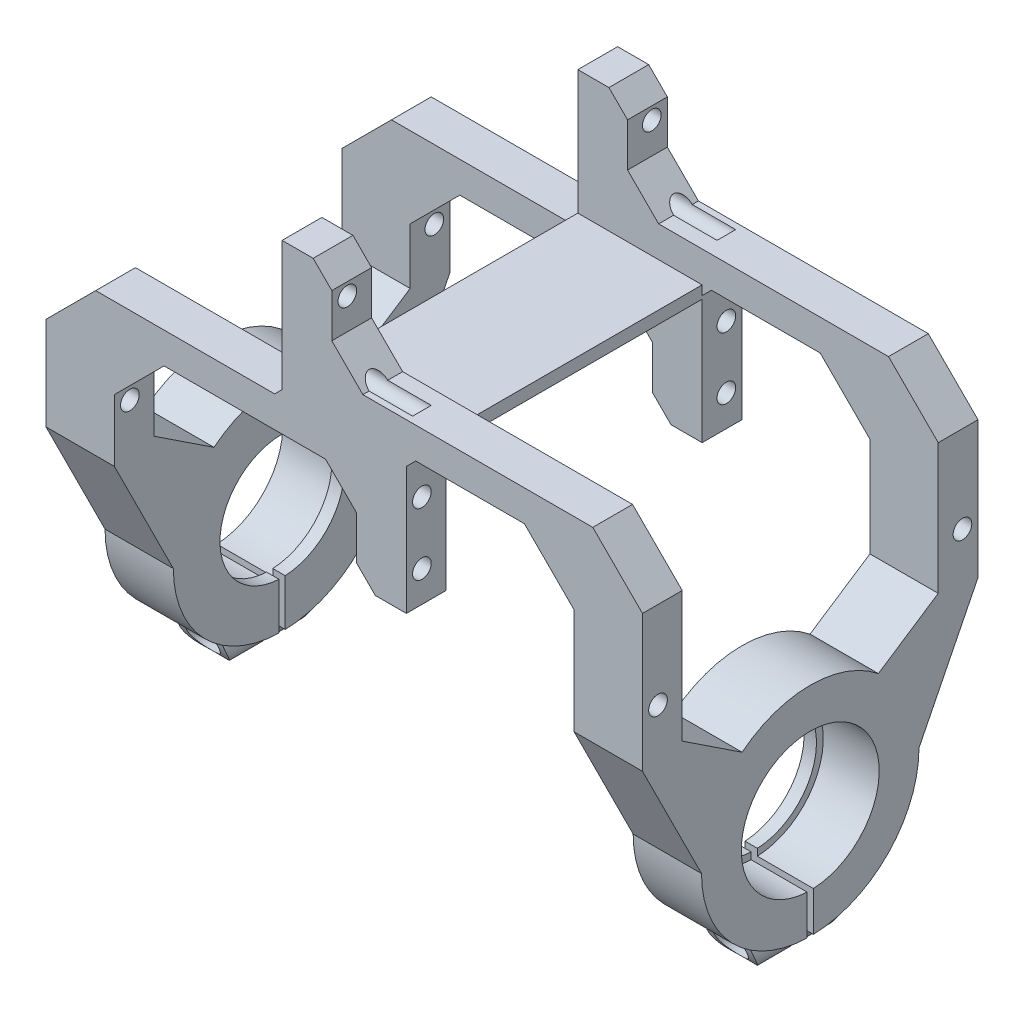
SolidWorks part; units mm, degrees
ref_plane "Front Plane" through (0, 0, 0) normal (0, 0, 1) x (1, 0, 0)
ref_plane "Top Plane" through (0, 0, 0) normal (0, 1, 0) x (1, 0, 0)
ref_plane "Right Plane" through (0, 0, 0) normal (1, 0, 0) x (0, 0, -1)
sketch "Sketch1" plane through (0, 0, 0) normal (0, 1, 0) x (1, 0, 0)
  line L1 (-10, -27) -> (10, -27)
  line L2 (-10, -27) -> (-10, 27)
  line L3 (-10, 27) -> (10, 27)
  line L4 (10, -27) -> (10, 27)
  line L5 (-10, -27) -> (10, 27) construction
  line L6 (-10, 27) -> (10, -27) construction
  point P0 (0, 0)
  dimension "D1" = 54
  dimension "D2" = 20
extrude "Boss-Extrude1" add sketch "Sketch1" along normal blind 2
sketch "Sketch2" plane through (0, 2, 0) normal (0, 1, 0) x (1, 0, 0)
  line L1 (-10, 27) -> (-2, 27)
  line L2 (-10, 27) -> (-10, 20.6)
  line L3 (-10, 20.6) -> (-2, 20.6)
  line L4 (-2, 27) -> (-2, 20.6)
  line L5 (-10, 27) -> (-2, 20.6) construction
  line L6 (-10, 20.6) -> (-2, 27) construction
  line L7 (-10, -27) -> (-2, -27)
  line L8 (-10, -27) -> (-10, -20.6)
  line L9 (-10, -20.6) -> (-2, -20.6)
  line L10 (-2, -27) -> (-2, -20.6)
  line L11 (-10, -27) -> (-2, -20.6) construction
  line L12 (-10, -20.6) -> (-2, -27) construction
  point P4 (-6, 23.8)
  point P10 (-6, -23.8)
  dimension "D1" = 6.4
  dimension "D2" = 8
  dimension "D3" = 8
  dimension "D4" = 6.4
extrude "Boss-Extrude2" add sketch "Sketch2" along normal blind 20
chamfer "Chamfer1" distance 5 angle 45 2 edges at (-2, 2, -23.8) (-2, 2, 23.8)
sketch "Sketch3" plane through (0, 0, 0) normal (0, -1, 0) x (1, 0, 0)
  line L1 (10, 27) -> (2, 27)
  line L2 (10, 27) -> (10, 20.6)
  line L3 (10, 20.6) -> (2, 20.6)
  line L4 (2, 27) -> (2, 20.6)
  line L5 (10, 27) -> (2, 20.6) construction
  line L6 (10, 20.6) -> (2, 27) construction
  line L7 (10, -27) -> (2, -27)
  line L8 (10, -27) -> (10, -20.6)
  line L9 (10, -20.6) -> (2, -20.6)
  line L10 (2, -27) -> (2, -20.6)
  line L11 (10, -27) -> (2, -20.6) construction
  line L12 (10, -20.6) -> (2, -27) construction
  point P4 (6, 23.8)
  point P10 (6, -23.8)
  dimension "D1" = 8
  dimension "D2" = 6.4
  dimension "D3" = 6.4
  dimension "D4" = 8
extrude "Boss-Extrude3" add sketch "Sketch3" along normal blind 20
chamfer "Chamfer2" distance 5 angle 45 2 edges at (2, 0, 23.8) (2, 0, -23.8)
chamfer "Chamfer3" distance 3 angle 45 4 edges at (2, -20, -23.8) (2, -20, 23.8) (-2, 22, -23.8) (-2, 22, 23.8)
sketch "Sketch5" plane through (0, 0, -27) normal (0, 0, -1) x (-1, 0, 0)
  line L0 (-10, 2) -> (-48, 2)
  line L1 (2, 7) -> (-48, 7)
  line L2 (-48, 7) -> (-48, 2)
  line L3 (2, 7) -> (-3, 2) construction
  line L4 (-10, 2) -> (-3, 2) construction
  line L5 (2, 7) -> (-3, 2)
  line L6 (-10, 2) -> (-3, 2)
  line L7 (0, 0) -> (0, 20) construction
  dimension "D1" = 48
  dimension "D2" = 20
extrude "Boss-Extrude4" add sketch "Sketch5" against normal up to surface (6.4 mm away) up to face at (-4.3333, 12.3333, -20.6)
sketch "Sketch7" plane through (0, 0, 27) normal (0, 0, 1) x (1, 0, 0)
  line L0 (3, 2) -> (-2, 7) construction
  line L1 (3, 2) -> (-2, 7)
  line L8 (-2, 7) -> (-2, 19)
  line L9 (-2, 19) -> (-5, 22)
  line L10 (-5, 22) -> (-10, 22)
  line L11 (-10, 22) -> (-10, 2)
  line L12 (-10, 2) -> (10, 2)
  line L13 (10, 2) -> (48, 2)
  line L14 (48, 2) -> (48, 7)
  line L15 (48, 7) -> (-2, 7)
  line L16 (-2, 7) -> (-2, 19)
  line L17 (-2, 19) -> (-5, 22)
  line L18 (-5, 22) -> (-10, 22)
  line L19 (-10, 22) -> (-10, 2)
  line L20 (-10, 2) -> (10, 2)
  line L21 (10, 2) -> (48, 2)
  line L22 (48, 2) -> (48, 7)
  line L23 (48, 7) -> (-2, 7)
  line M13 (10, 2) -> (3, 2)
  line M14 (3, 2) -> (-2, 7)
  dimension "D1" = 0
extrude "Boss-Extrude6" add sketch "Sketch7" against normal up to surface (6.4 mm away) contours L22 L23 L21 M14 M13 up to face at (-4.3333, 12.3333, 20.6)
chamfer "Chamfer4" distance 5 angle 45 2 edges at (-2, 7, -23.8) (-2, 7, 23.8)
chamfer "Chamfer5" distance 1.5 angle 45 2 edges at (10, 2, 23.8) (10, 2, -23.8)
sketch "Sketch6" plane through (48, 0, 0) normal (1, 0, 0) x (0, 0, -1)
  line L0 (27, 2) -> (27, -23)
  line L1 (27, -23) -> (17.5, -42)
  line L2 (20.6, 2) -> (20.6, -22)
  line L3 (20.6, 2) -> (27, 2) construction
  line L4 (20.6, 2) -> (27, 2)
  line L5 (20.6, -22) -> (10.9653, -28.3614)
  line L6 (0, 0) -> (0, 30) construction
  line L7 (-20.6, 0) -> (20.6, 0) construction
  line L8 (-20.6, -22) -> (-10.9653, -28.3614)
  line L9 (-20.6, 2) -> (-27, 2)
  line L10 (-20.6, 2) -> (-20.6, -22)
  line L11 (-27, -23) -> (-17.5, -42)
  line L12 (-27, 2) -> (-27, -23)
  arc A0 (10.9653, -28.3614) -> (-10.9653, -28.3614) centre (0, -42) ccw
  circle A1 centre (0, -42) radius 11.1
  arc A2 (-17.5, -42) -> (17.5, -42) centre (0, -42) ccw
  dimension "D2" = 22.2
  dimension "D3" = 35
  dimension "D1" = 25
  dimension "D4" = 42
  dimension "D5" = 24
  dimension "D6" = 30
  dimension "D7" = 30
extrude "Boss-Extrude5" add sketch "Sketch6" against normal blind 11
chamfer "Chamfer6" distance 8 angle 45 4 edges at (48, 7, 23.8) (48, 7, -23.8) (37, 2, 23.8) (37, 2, -23.8)
sketch "Sketch8" plane through (0, 0, -27) normal (0, 0, -1) x (-1, 0, 0)
  line L0 (10, 0) -> (48, 0)
  line L1 (48, 0) -> (48, -5)
  line L2 (48, -5) -> (-2, -5)
  line L3 (-2, -5) -> (3, 0)
  line L4 (3, 0) -> (10, 0)
  line L6 (0, 0) -> (0, 20) construction
  dimension "D1" = 48
  dimension "D2" = 20
extrude "Boss-Extrude7" add sketch "Sketch8" against normal up to surface (6.4 mm away) up to face at (4.3333, -10.3333, -20.6)
sketch "Sketch9" plane through (0, 0, 27) normal (0, 0, 1) x (1, 0, 0)
  line L0 (-3, 0) -> (2, -5) construction
  line L1 (-3, 0) -> (2, -5)
  line L7 (10, 0) -> (-10, 0)
  line L8 (2, -5) -> (2, -17)
  line L9 (2, -17) -> (5, -20)
  line L10 (5, -20) -> (10, -20)
  line L11 (10, -20) -> (10, 0)
  line L12 (10, 0) -> (-10, 0)
  line L13 (-10, 0) -> (-48, 0)
  line L15 (-10, 0) -> (-48, 0)
  line L16 (2, -5) -> (2, -17)
  line L17 (2, -17) -> (5, -20)
  line L18 (5, -20) -> (10, -20)
  line L19 (10, -20) -> (10, 0)
  line L20 (10, 0) -> (-10, 0)
  line L24 (-48, 0) -> (-48, -5)
  line L25 (-48, -5) -> (2, -5)
  line L26 (2, -5) -> (2, -17)
  line L27 (10, 0) -> (-10, 0)
  line L28 (-10, 0) -> (-48, 0)
  line L29 (-48, 0) -> (-48, -5)
  line L30 (-48, -5) -> (2, -5)
  line L35 (-10, 0) -> (-48, 0)
  line L36 (-48, 0) -> (-48, -5)
  line L37 (-48, 0) -> (-48, -5)
  line L38 (-48, -5) -> (2, -5)
  line L39 (-48, -5) -> (2, -5)
  line L40 (2, -5) -> (2, -17)
  line L41 (2, -17) -> (5, -20)
  line L42 (2, -17) -> (5, -20)
  line L43 (5, -20) -> (10, -20)
  line L44 (5, -20) -> (10, -20)
  line L45 (10, -20) -> (10, 0)
  line L46 (10, -20) -> (10, 0)
  line M17 (-10, 0) -> (-3, 0)
  line M18 (-3, 0) -> (2, -5)
  dimension "D1" = 0
  dimension "D2" = 0
extrude "Boss-Extrude8" add sketch "Sketch9" against normal up to surface (6.4 mm away) contours L37 L39 L35 M18 M17 up to face at (4.3333, -10.3333, 20.6)
sketch "Sketch10" plane through (-48, 0, 0) normal (-1, 0, 0) x (0, 0, 1)
  line L1 (-27, -5) -> (-20.6, -5) construction
  line L2 (-27, -5) -> (-27, -6)
  line L3 (-27, -6) -> (-20.6, -6) construction
  line L4 (-20.6, -5) -> (-20.6, 0)
  line L5 (-20.6, 0) -> (-27, 0)
  line L6 (-27, 0) -> (-27, -5)
  line L7 (-27, -5) -> (-20.6, -5)
  line L8 (-20.6, -5) -> (-20.6, 0)
  line L9 (-20.6, 0) -> (-27, 0)
  line L10 (27, -23) -> (27, -6)
  line L11 (27, -6) -> (20.6, -6)
  line L12 (20.6, -6) -> (20.6, -22)
  line L13 (20.6, -22) -> (10.9653, -28.3614)
  line L14 (-10.9653, -28.3614) -> (-20.6, -22)
  line L15 (-20.6, -22) -> (-20.6, -6)
  line L16 (-20.6, -6) -> (-27, -6)
  line L17 (-27, -6) -> (-27, -23)
  line L18 (-27, -23) -> (-17.5, -42)
  line L19 (17.5, -42) -> (27, -23)
  line L20 (27, -23) -> (27, -6)
  line L21 (27, -6) -> (20.6, -6) construction
  line L22 (20.6, -6) -> (20.6, -22)
  line L23 (20.6, -22) -> (10.9653, -28.3614)
  line L24 (-10.9653, -28.3614) -> (-20.6, -22)
  line L25 (-20.6, -22) -> (-20.6, -6)
  line L26 (-20.6, -6) -> (-27, -6) construction
  line L27 (-27, -6) -> (-27, -23)
  line L28 (-27, -23) -> (-17.5, -42)
  line L29 (17.5, -42) -> (27, -23)
  line L30 (-27, 0) -> (-27, -5)
  line L31 (-27, -5) -> (-20.6, -5) construction
  line L32 (-20.6, -5) -> (-20.6, -6)
  line L33 (-27, -5) -> (-20.6, -6) construction
  line L34 (-27, -6) -> (-20.6, -5) construction
  line L35 (27, -6) -> (20.6, -6) construction
  line L36 (27, -6) -> (27, 0)
  line L37 (27, 0) -> (20.6, 0)
  line L38 (20.6, -6) -> (20.6, 0)
  line L39 (27, -6) -> (20.6, 0) construction
  line L40 (27, 0) -> (20.6, -6) construction
  circle A0 centre (0, -42) radius 11.1 construction
  circle A1 centre (0, -42) radius 11.1
  arc A2 (10.9653, -28.3614) -> (-10.9653, -28.3614) centre (0, -42) ccw
  arc A3 (-17.5, -42) -> (17.5, -42) centre (0, -42) ccw
  arc A4 (10.9653, -28.3614) -> (-10.9653, -28.3614) centre (0, -42) ccw
  arc A5 (-17.5, -42) -> (17.5, -42) centre (0, -42) ccw
  point P19 (-23.8, -5.5)
  point P22 (23.8, -3)
  line M14 (20.6, -5) -> (27, -5)
  dimension "D1" = 0
  dimension "D2" = 0
extrude "Boss-Extrude9" add sketch "Sketch10" against normal blind 11 contours L28 A5 L29 L20 L22 L23 A4 L24 L25 L31 L27 M14
sketch "Sketch11" plane through (-48, 0, 0) normal (-1, 0, 0) x (0, 0, 1)
  circle A0 centre (0, -42) radius 11.1 construction
  circle A1 centre (0, -42) radius 11.1
  circle A2 centre (0, -42) radius 10
  dimension "D1" = 20
extrude "Boss-Extrude10" add sketch "Sketch11" along normal blind 2 from surface at -11 starting at face at (-37, -22.0301, 0)
sketch "Sketch12" plane through (48, 0, 0) normal (1, 0, 0) x (0, 0, -1)
  circle A0 centre (0, -42) radius 11.1 construction
  circle A1 centre (0, -42) radius 11.1
  circle A2 centre (0, -42) radius 10 construction
  circle A3 centre (0, -42) radius 10
extrude "Boss-Extrude11" add sketch "Sketch12" along normal blind 2 from surface at -11 starting at face at (37, -42, -11.1)
chamfer "Chamfer7" distance 8 angle 45 4 edges at (-48, 0, -23.8) (-48, 0, 23.8) (-37, -5, -23.8) (-37, -5, 23.8)
chamfer "Chamfer8" distance 5 angle 45 2 edges at (2, -5, -23.8) (2, -5, 23.8)
sketch "Sketch13" plane through (10, 0, 0) normal (1, 0, 0) x (0, 0, -1)
  circle A0 centre (24.5, -15) radius 1.5
  circle A1 centre (24.5, -5) radius 1.5
  circle A2 centre (-24.5, -15) radius 1.5
  circle A3 centre (-24.5, -5) radius 1.5
  circle A4 centre (-24.5, 7) radius 1.5
  circle A5 centre (-24.5, 17) radius 1.5
  circle A6 centre (24.5, 7) radius 1.5
  circle A7 centre (24.5, 17) radius 1.5
  dimension "D1" = 3
  dimension "D2" = 3
extrude "Cut-Extrude1" cut sketch "Sketch13" against normal blind 20
chamfer "Chamfer9" distance 1.2 angle 45 2 edges at (-10, 0, 23.8) (-10, 0, -23.8)
sketch "Sketch14" plane through (0, 0, 0) normal (0, 0, 1) x (1, 0, 0)
  line L2 (-37, -59.5) -> (-37, -42) construction
  line L4 (-48, -42) -> (-48, -59.5) construction
  line L5 (-48, -42) -> (-48, -59.5)
  line L6 (-37, -59.5) -> (-37, -42)
  line L7 (-48, -59.5) -> (-37, -59.5) construction
  circle A0 centre (-42.5, -59.5) radius 1.5
  circle A1 centre (-42.5, -59.5) radius 3.75
  point P3 (-42.5, -59.5)
  dimension "D1" = 7.5
  dimension "D2" = 3
extrude "Boss-Extrude12" add sketch "Sketch14" against normal blind 8 and the other way blind 8 contours L7 A1 A0 | A1 L7 A0
sketch "Sketch15" plane through (0, 0, -8) normal (0, 0, -1) x (-1, 0, 0)
  circle A0 centre (42.5, -59.5) radius 1.5 construction
  circle A1 centre (42.5, -59.5) radius 1.5
extrude "Cut-Extrude2" cut sketch "Sketch15" against normal through all
sketch "Sketch16" plane through (-48, 0, 0) normal (-1, 0, 0) x (0, 0, 1)
  line L0 (-8, -63.25) -> (8, -63.25) construction
  line L1 (4.5, -63.25) -> (8, -63.25)
  line L2 (8, -63.25) -> (8, -57.5644)
  line L3 (0, -63.25) -> (0, -59.5) construction
  line L4 (-8, -63.25) -> (-8, -57.5644)
  line L5 (-4.5, -63.25) -> (-8, -63.25)
  arc A0 (-17.5, -42) -> (17.5, -42) centre (0, -42) ccw construction
  spline S0 degree 2 poles (8, -57.5644) (7.1886, -61.0116) (4.5, -63.25) knots 0 0 0 1 1 1
  spline S1 degree 2 poles (-8, -57.5644) (-7.1886, -61.0116) (-4.5, -63.25) knots 0 0 0 1 1 1
  dimension "D1" = 2.2
  dimension "D2" = 1.5
  dimension "D3" = 3.5
extrude "Cut-Extrude3" cut sketch "Sketch16" against normal through all
sketch "Sketch17" plane through (-48, 0, 0) normal (-1, 0, 0) x (0, 0, 1)
  line L0 (-4.5, -63.25) -> (4.5, -63.25) construction
  line L1 (0.5, -78.25) -> (-0.5, -78.25)
  line L2 (0.5, -78.25) -> (0.5, -48.25)
  line L3 (0.5, -48.25) -> (-0.5, -48.25)
  line L4 (-0.5, -78.25) -> (-0.5, -48.25)
  line L5 (0.5, -78.25) -> (-0.5, -48.25) construction
  line L6 (0.5, -48.25) -> (-0.5, -78.25) construction
  line L7 (-4.5, -63.25) -> (4.5, -63.25)
  point P4 (0, -63.25)
  point P8 (0, -63.25)
  arc M9 (-17.5, -42) -> (17.5, -42) centre (0, -42) ccw
  circle M17 centre (0, -42) radius 11.1
  dimension "D1" = 30
  dimension "D2" = 1
extrude "Cut-Extrude4" cut sketch "Sketch17" against normal through all contours L7 L4 L1 L2 | L4 L7 L2 M9 | L4 L2 M9 M17 | L4 L2 L3 M17
sketch "Sketch18" plane through (0, 0, -0.5) normal (0, 0, 1) x (1, 0, 0)
  circle A0 centre (-42.5, -59.5) radius 2.6
  dimension "D1" = 5.2
extrude "Cut-Extrude5" cut sketch "Sketch18" against normal blind 8 from offset 4.5 offset against normal yes
mirror "Mirror1" about plane through (0, 0, 0) normal (1, 0, 0) of "Boss-Extrude12", "Cut-Extrude2", "Cut-Extrude3", "Cut-Extrude5"
sketch "Sketch19" plane through (-48, 0, 0) normal (-1, 0, 0) x (0, 0, 1)
  line L0 (-0.5, -63.25) -> (-0.5, -59.4929) construction
  line L1 (0.5, -51.9875) -> (-0.5, -51.9875)
  line L2 (0.5, -51.9875) -> (0.5, -63.9875)
  line L3 (0.5, -63.9875) -> (-0.5, -63.9875)
  line L4 (-0.5, -51.9875) -> (-0.5, -63.9875)
  line L5 (0.5, -51.9875) -> (-0.5, -63.9875) construction
  line L6 (0.5, -63.9875) -> (-0.5, -51.9875) construction
  point P4 (0, -57.9875)
  dimension "D1" = 12
extrude "Cut-Extrude6" cut sketch "Sketch19" against normal through all both and the other way through all
sketch "Sketch20" plane through (0, 0, -5) normal (0, 0, -1) x (-1, 0, 0)
  circle A1 centre (42.5, -59.5) radius 2.6
  circle A2 centre (42.5, -59.5) radius 2.6
  circle A3 centre (-42.5, -59.5) radius 2.6
  circle A4 centre (-42.5, -59.5) radius 2.6
  dimension "D1" = 0
  dimension "D2" = 0
extrude "Cut-Extrude7" cut sketch "Sketch20" against normal through all from offset 9.5 offset against normal yes
sketch "Sketch21" plane through (2, 0, 0) normal (-1, 0, 0) x (0, 0, 1)
  circle A0 centre (24.5, -15) radius 1.5 construction
  circle A1 centre (24.5, -15) radius 1.5
  circle A2 centre (-24.5, -15) radius 1.5 construction
  circle A3 centre (-24.5, -15) radius 1.5
extrude "Cut-Extrude8" cut sketch "Sketch21" against normal through all both and the other way through all
sketch "Sketch22" plane through (0, 0, -5) normal (0, 0, -1) x (-1, 0, 0)
  line L1 (-44.0877, -62.25) -> (-40.9123, -62.25)
  line L2 (-40.9123, -62.25) -> (-39.3246, -59.5)
  line L3 (-39.3246, -59.5) -> (-40.9123, -56.75)
  line L4 (-40.9123, -56.75) -> (-44.0877, -56.75)
  line L5 (-44.0877, -56.75) -> (-45.6754, -59.5)
  line L6 (-45.6754, -59.5) -> (-44.0877, -62.25)
  line L7 (40.9123, -62.25) -> (44.0877, -62.25)
  line L8 (44.0877, -62.25) -> (45.6754, -59.5)
  line L9 (45.6754, -59.5) -> (44.0877, -56.75)
  line L10 (44.0877, -56.75) -> (40.9123, -56.75)
  line L11 (40.9123, -56.75) -> (39.3246, -59.5)
  line L12 (39.3246, -59.5) -> (40.9123, -62.25)
  circle A0 centre (-42.5, -59.5) radius 2.75 construction
  circle A1 centre (42.5, -59.5) radius 2.75 construction
  dimension "D1" = 5.5
  dimension "D2" = 5.5
extrude "Cut-Extrude9" cut sketch "Sketch22" along normal blind 10
